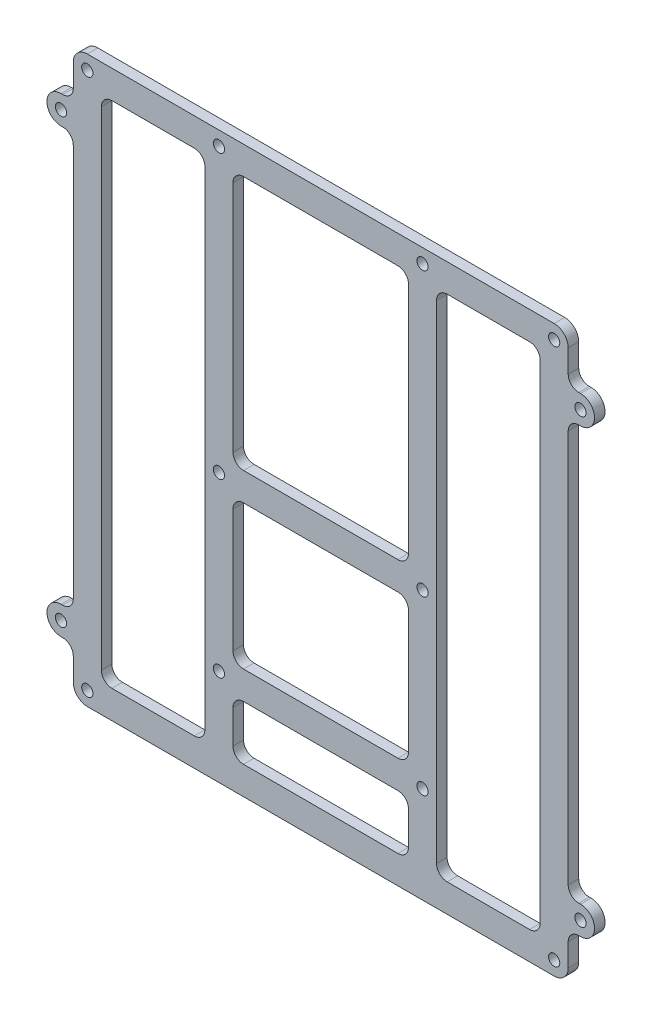
SolidWorks part; units mm, degrees
material "Thornel Mat VMA"
ref_plane "Front Plane" through (0, 0, 0) normal (0, 0, 1) x (1, 0, 0)
ref_plane "Top Plane" through (0, 0, 0) normal (0, 1, 0) x (1, 0, 0)
ref_plane "Right Plane" through (0, 0, 0) normal (1, 0, 0) x (0, 0, -1)
sketch "Model" plane through (0, 0, 0) normal (0, 0, 1) x (1, 0, 0)
  line L0 (-62.5, 69.5) -> (-62.5, -69.5)
  line L1 (-70.5, 76.5) -> (-70.5, 70)
  line L2 (-70.5, 56) -> (-70.5, -56)
  line L3 (-70.5, -70) -> (-70.5, -76.5)
  line L4 (-59.5, -72.5) -> (-36, -72.5)
  line L5 (-22, -72.5) -> (22, -72.5)
  line L6 (36, -72.5) -> (59.5, -72.5)
  line L7 (-66.5, -80.5) -> (66.5, -80.5)
  line L8 (62.5, -69.5) -> (62.5, 69.5)
  line L9 (70.5, -76.5) -> (70.5, -70)
  line L10 (70.5, -56) -> (70.5, 56)
  line L11 (70.5, 70) -> (70.5, 76.5)
  line L12 (59.5, 72.5) -> (36, 72.5)
  line L13 (22, 72.5) -> (-22, 72.5)
  line L14 (-36, 72.5) -> (-59.5, 72.5)
  line L15 (66.5, 80.5) -> (-66.5, 80.5)
  line L16 (-74, 67) -> (-73.5, 67)
  line L17 (-74, 59) -> (-73.5, 59)
  line L18 (-74, -59) -> (-73.5, -59)
  line L19 (-74, -67) -> (-73.5, -67)
  line L20 (74, 67) -> (73.5, 67)
  line L21 (74, 59) -> (73.5, 59)
  line L22 (74, -59) -> (73.5, -59)
  line L23 (74, -67) -> (73.5, -67)
  line L24 (-25, -11) -> (-25, -46)
  line L25 (-22, -49) -> (22, -49)
  line L26 (25, -46) -> (25, -11)
  line L27 (22, -8) -> (-22, -8)
  line L28 (-33, 69.5) -> (-33, -69.5)
  line L29 (33, 69.5) -> (33, -69.5)
  line L30 (22, 0) -> (-22, 0)
  line L31 (-22, -57) -> (22, -57)
  line L32 (-25, 3) -> (-25, 69.5)
  line L33 (25, 3) -> (25, 69.5)
  line L34 (-25, -60) -> (-25, -69.5)
  line L35 (25, -60) -> (25, -69.5)
  circle A0 centre (66.5, 76.5) radius 1.6
  circle A1 centre (66.5, -76.5) radius 1.6
  circle A2 centre (-66.5, 76.5) radius 1.6
  circle A3 centre (-66.5, -76.5) radius 1.6
  arc A4 (-59.5, 72.5) -> (-62.5, 69.5) centre (-59.5, 69.5) ccw
  arc A5 (-73.5, 67) -> (-70.5, 70) centre (-73.5, 70) ccw
  arc A6 (-73.5, -59) -> (-70.5, -56) centre (-73.5, -56) ccw
  arc A7 (-70.5, 56) -> (-73.5, 59) centre (-73.5, 56) ccw
  arc A8 (-62.5, -69.5) -> (-59.5, -72.5) centre (-59.5, -69.5) ccw
  arc A9 (22, -72.5) -> (25, -69.5) centre (22, -69.5) ccw
  arc A10 (-25, -69.5) -> (-22, -72.5) centre (-22, -69.5) ccw
  arc A11 (62.5, 69.5) -> (59.5, 72.5) centre (59.5, 69.5) ccw
  arc A12 (59.5, -72.5) -> (62.5, -69.5) centre (59.5, -69.5) ccw
  arc A13 (73.5, -67) -> (70.5, -70) centre (73.5, -70) ccw
  arc A14 (70.5, -56) -> (73.5, -59) centre (73.5, -56) ccw
  arc A15 (73.5, 59) -> (70.5, 56) centre (73.5, 56) ccw
  arc A16 (70.5, 70) -> (73.5, 67) centre (73.5, 70) ccw
  circle A17 centre (-74, 63) radius 1.6
  circle A18 centre (74, 63) radius 1.6
  circle A19 centre (-74, -63) radius 1.6
  circle A20 centre (74, -63) radius 1.6
  arc A21 (-66.5, 80.5) -> (-70.5, 76.5) centre (-66.5, 76.5) ccw
  arc A22 (70.5, 76.5) -> (66.5, 80.5) centre (66.5, 76.5) ccw
  arc A23 (-70.5, -76.5) -> (-66.5, -80.5) centre (-66.5, -76.5) ccw
  arc A24 (66.5, -80.5) -> (70.5, -76.5) centre (66.5, -76.5) ccw
  arc A25 (-74, 67) -> (-74, 59) centre (-74, 63) ccw
  arc A26 (-74, -59) -> (-74, -67) centre (-74, -63) ccw
  arc A27 (74, -67) -> (74, -59) centre (74, -63) ccw
  arc A28 (74, 59) -> (74, 67) centre (74, 63) ccw
  arc A29 (-70.5, -70) -> (-73.5, -67) centre (-73.5, -70) ccw
  circle A30 centre (29, -53) radius 1.6
  circle A31 centre (29, -4) radius 1.6
  circle A32 centre (-29, -53) radius 1.6
  circle A33 centre (-29, -4) radius 1.6
  arc A34 (-25, -46) -> (-22, -49) centre (-22, -46) ccw
  arc A35 (-22, -8) -> (-25, -11) centre (-22, -11) ccw
  arc A36 (22, -49) -> (25, -46) centre (22, -46) ccw
  arc A37 (25, -11) -> (22, -8) centre (22, -11) ccw
  arc A38 (-36, -72.5) -> (-33, -69.5) centre (-36, -69.5) ccw
  arc A39 (-33, 69.5) -> (-36, 72.5) centre (-36, 69.5) ccw
  arc A40 (36, 72.5) -> (33, 69.5) centre (36, 69.5) ccw
  arc A41 (33, -69.5) -> (36, -72.5) centre (36, -69.5) ccw
  arc A42 (22, 0) -> (25, 3) centre (22, 3) ccw
  arc A43 (-25, 3) -> (-22, 0) centre (-22, 3) ccw
  arc A44 (-22, 72.5) -> (-25, 69.5) centre (-22, 69.5) ccw
  arc A45 (25, 69.5) -> (22, 72.5) centre (22, 69.5) ccw
  arc A46 (-22, -57) -> (-25, -60) centre (-22, -60) ccw
  arc A47 (25, -60) -> (22, -57) centre (22, -60) ccw
  circle A48 centre (29, 76.5) radius 1.6
  circle A49 centre (-29, 76.5) radius 1.6
extrude "Boss-Extrude1" add sketch "Model" along normal blind 3
